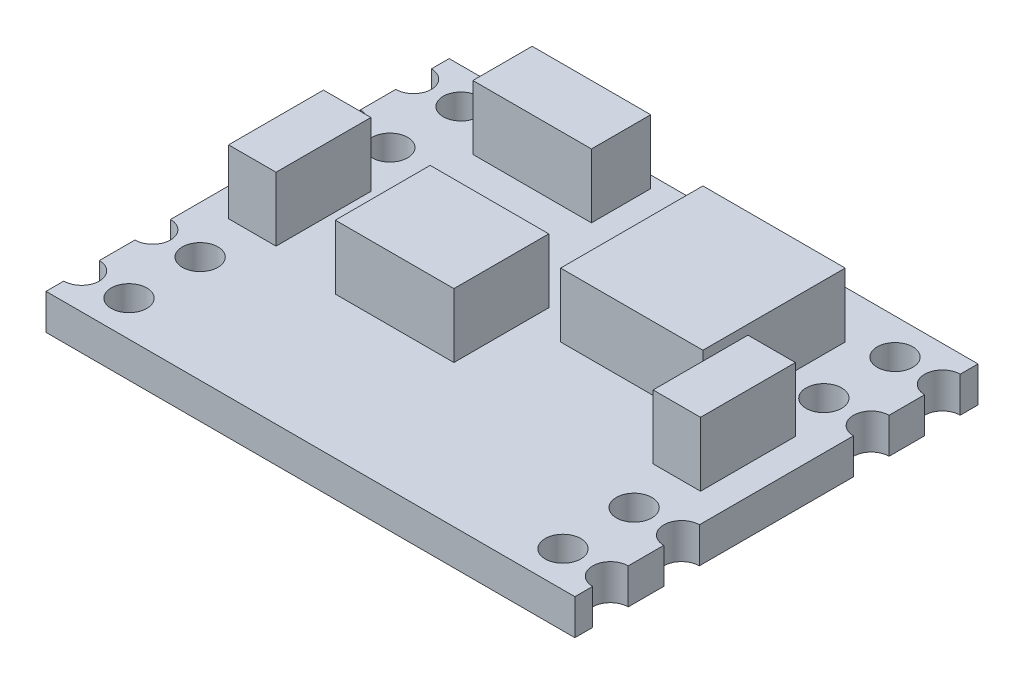
SolidWorks part; units mm, degrees
ref_plane "정면" through (0, 0, 0) normal (0, 0, 1) x (1, 0, 0)
ref_plane "윗면" through (0, 0, 0) normal (0, 1, 0) x (1, 0, 0)
ref_plane "우측면" through (0, 0, 0) normal (1, 0, 0) x (0, 0, -1)
sketch "스케치1" plane through (0, 0, 0) normal (0, 1, 0) x (1, 0, 0)
  line L1 (-11.15, 8.5) -> (11.15, 8.5)
  line L2 (-11.15, 8.5) -> (-11.15, -8.5)
  line L3 (-11.15, -8.5) -> (11.15, -8.5)
  line L4 (11.15, 8.5) -> (11.15, -8.5)
  line L5 (-11.15, 8.5) -> (11.15, -8.5) construction
  line L6 (-11.15, -8.5) -> (11.15, 8.5) construction
  point P0 (0, 0)
  dimension "D1" = 17
  dimension "D2" = 22.3
extrude "보스-돌출1" add sketch "스케치1" along normal blind 1.5
sketch "스케치2" plane through (0, 1.5, 0) normal (0, 1, 0) x (1, 0, 0)
  line L0 (-11.15, 8.5) -> (-11.15, -8.5) construction
  line L1 (1.55, 6.5) -> (7.55, 6.5)
  line L2 (1.55, 6.5) -> (1.55, 0.5)
  line L3 (1.55, 0.5) -> (7.55, 0.5)
  line L4 (7.55, 6.5) -> (7.55, 0.5)
  line L5 (1.55, 6.5) -> (7.55, 0.5) construction
  line L6 (1.55, 0.5) -> (7.55, 6.5) construction
  line L7 (-7.15, 8) -> (-2.15, 8)
  line L8 (-7.15, 8) -> (-7.15, 5.5)
  line L9 (-7.15, 5.5) -> (-2.15, 5.5)
  line L10 (-2.15, 8) -> (-2.15, 5.5)
  line L11 (-7.15, 8) -> (-2.15, 5.5) construction
  line L12 (-7.15, 5.5) -> (-2.15, 8) construction
  line L13 (-9.95, 2) -> (-7.95, 2)
  line L14 (-9.95, 2) -> (-9.95, -2)
  line L15 (-9.95, -2) -> (-7.95, -2)
  line L16 (-7.95, 2) -> (-7.95, -2)
  line L17 (-9.95, 2) -> (-7.95, -2) construction
  line L18 (-9.95, -2) -> (-7.95, 2) construction
  line L19 (9.95, 2) -> (7.95, 2)
  line L20 (9.95, 2) -> (9.95, -2)
  line L21 (9.95, -2) -> (7.95, -2)
  line L22 (7.95, 2) -> (7.95, -2)
  line L23 (9.95, 2) -> (7.95, -2) construction
  line L24 (9.95, -2) -> (7.95, 2) construction
  line L25 (-4.95, 1.5) -> (0.05, 1.5)
  line L26 (-4.95, 1.5) -> (-4.95, -2.5)
  line L27 (-4.95, -2.5) -> (0.05, -2.5)
  line L28 (0.05, 1.5) -> (0.05, -2.5)
  line L29 (-4.95, 1.5) -> (0.05, -2.5) construction
  line L30 (-4.95, -2.5) -> (0.05, 1.5) construction
  line L31 (11.15, -8.5) -> (11.15, 8.5) construction
  line L32 (11.15, 8.5) -> (-11.15, 8.5) construction
  point P0 (4.55, 3.5)
  point P5 (-4.65, 6.75)
  point P10 (-8.95, 0)
  point P15 (8.95, 0)
  point P20 (-2.45, -0.5)
  point P29 (-11.15, 0)
  point P30 (-9.95, 0)
  dimension "D1" = 2
  dimension "D2" = 2
  dimension "D3" = 1.2
  dimension "D4" = 1.2
  dimension "D5" = 4
  dimension "D6" = 4
  dimension "D7" = 5
  dimension "D8" = 3
  dimension "D9" = 0.5
  dimension "D10" = 6
  dimension "D11" = 6
  dimension "D12" = 1.5
  dimension "D13" = 5
  dimension "D14" = 2.5
  dimension "D15" = 4
  dimension "D16" = 0.5
  dimension "D17" = 2
extrude "보스-돌출2" add sketch "스케치2" along normal blind 2.7
sketch "스케치3" plane through (0, 1.5, 0) normal (0, 1, 0) x (1, 0, 0)
  line L0 (11.15, 8.5) -> (-11.15, 8.5) construction
  line L1 (-11.15, 4) -> (-9.15, 4) construction
  line L2 (-11.15, 4) -> (-11.15, 7) construction
  line L3 (-11.15, 7) -> (-9.15, 7) construction
  line L4 (-9.15, 4) -> (-9.15, 7) construction
  line L5 (-11.15, 4) -> (-9.15, 7) construction
  line L6 (-11.15, 7) -> (-9.15, 4) construction
  line L7 (-10.15, 5.5) -> (10.15, 5.5) construction
  line L8 (-10.15, 5.5) -> (-10.15, -5.5) construction
  line L9 (-10.15, -5.5) -> (10.15, -5.5) construction
  line L10 (10.15, 5.5) -> (10.15, -5.5) construction
  line L11 (-11.15, -8.5) -> (11.15, -8.5) construction
  line L12 (-11.15, 8.5) -> (-11.15, -8.5) construction
  line L13 (11.15, -8.5) -> (11.15, 8.5) construction
  line L15 (-11.15, -4) -> (-9.15, -4) construction
  line L16 (-11.15, -4) -> (-11.15, -7) construction
  line L17 (-11.15, -7) -> (-9.15, -7) construction
  line L18 (-9.15, -4) -> (-9.15, -7) construction
  line L19 (-11.15, -4) -> (-9.15, -7) construction
  line L20 (-11.15, -7) -> (-9.15, -4) construction
  line L21 (9.15, -4) -> (11.15, -4) construction
  line L22 (9.15, -4) -> (9.15, -7) construction
  line L23 (9.15, -7) -> (11.15, -7) construction
  line L24 (11.15, -4) -> (11.15, -7) construction
  line L25 (9.15, -4) -> (11.15, -7) construction
  line L26 (9.15, -7) -> (11.15, -4) construction
  line L27 (9.15, 7) -> (11.15, 7) construction
  line L28 (9.15, 7) -> (9.15, 4) construction
  line L29 (9.15, 4) -> (11.15, 4) construction
  line L30 (11.15, 7) -> (11.15, 4) construction
  line L31 (9.15, 7) -> (11.15, 4) construction
  line L32 (9.15, 4) -> (11.15, 7) construction
  circle A0 centre (-11.15, 7) radius 0.75
  circle A1 centre (-11.15, 4) radius 0.75
  circle A2 centre (-9.15, 7) radius 0.75
  circle A3 centre (-9.15, 4) radius 0.75
  circle A4 centre (9.15, 7) radius 0.75
  circle A5 centre (11.15, 7) radius 0.75
  circle A6 centre (9.15, 4) radius 0.75
  circle A7 centre (11.15, 4) radius 0.75
  circle A8 centre (-11.15, -4) radius 0.75
  circle A9 centre (-9.15, -4) radius 0.75
  circle A10 centre (-9.15, -7) radius 0.75
  circle A11 centre (-11.15, -7) radius 0.75
  circle A12 centre (11.15, -4) radius 0.75
  circle A13 centre (9.15, -4) radius 0.75
  circle A14 centre (9.15, -7) radius 0.75
  circle A15 centre (11.15, -7) radius 0.75
  point P0 (-10.15, 5.5)
  dimension "D7" = 1.5
  dimension "D1" = 3
  dimension "D2" = 3
  dimension "D3" = 3
  dimension "D4" = 1
  dimension "D5" = 1
  dimension "D6" = 2
extrude "컷-돌출1" cut sketch "스케치3" against normal through all
